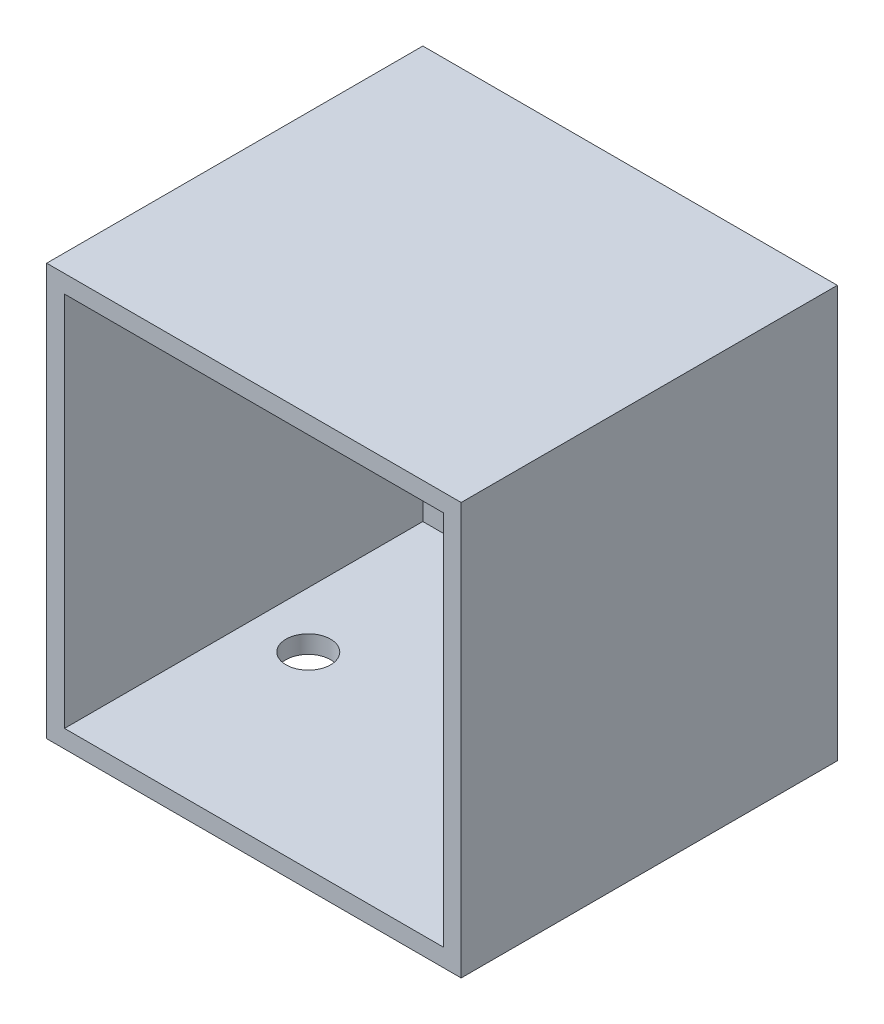
SolidWorks part; units mm, degrees
ref_plane "Front Plane" through (0, 0, 0) normal (0, 0, 1) x (1, 0, 0)
ref_plane "Top Plane" through (0, 0, 0) normal (0, 1, 0) x (1, 0, 0)
ref_plane "Right Plane" through (0, 0, 0) normal (1, 0, 0) x (0, 0, -1)
sketch "Sketch2" plane through (0, 0, 0) normal (0, 1, 0) x (1, 0, 0)
  line L0 (-55, 0) -> (55, 0) construction
  line L1 (-23.25, -21.1) -> (23.25, -21.1)
  line L2 (-23.25, -21.1) -> (-23.25, 21.1)
  line L3 (-23.25, 21.1) -> (23.25, 21.1)
  line L4 (23.25, -21.1) -> (23.25, 21.1)
  line L5 (-23.25, -21.1) -> (23.25, 21.1) construction
  line L6 (-23.25, 21.1) -> (23.25, -21.1) construction
  line L7 (0, -55) -> (0, 55) construction
  circle A0 centre (-15, 0) radius 2.5
  circle A1 centre (15, 0) radius 2.5
  point P1 (0, 0)
  dimension "D3" = 5
  dimension "D1" = 46.5
  dimension "D2" = 42.2
  dimension "D4" = 15
extrude "Boss-Extrude1" add sketch "Sketch2" along normal blind 2
sketch "Sketch3" plane through (0, 2, 0) normal (0, 1, 0) x (1, 0, 0)
  line L0 (-23.25, -21.1) -> (-21.25, -21.1)
  line L1 (-23.25, -21.1) -> (23.25, -21.1) construction
  line L2 (-21.25, -21.1) -> (-21.25, 19.1)
  line L3 (-21.25, 19.1) -> (21.25, 19.1)
  line L4 (21.25, 19.1) -> (21.25, -21.1)
  line L5 (21.25, -21.1) -> (23.25, -21.1)
  line L6 (23.25, -21.1) -> (23.25, 21.1)
  line L7 (23.25, 21.1) -> (-23.25, 21.1)
  line L8 (-23.25, 21.1) -> (-23.25, -21.1)
  dimension "D1" = 2
  dimension "D2" = 2
  dimension "D3" = 2
extrude "Boss-Extrude2" add sketch "Sketch3" along normal blind 42.2
sketch "Sketch4" plane through (0, 44.2, 0) normal (0, 1, 0) x (1, 0, 0)
  line L1 (-23.25, 21.1) -> (23.25, 21.1)
  line L2 (-23.25, 21.1) -> (-23.25, -21.1)
  line L3 (-23.25, -21.1) -> (23.25, -21.1)
  line L4 (23.25, 21.1) -> (23.25, -21.1)
extrude "Boss-Extrude3" add sketch "Sketch4" along normal blind 2
